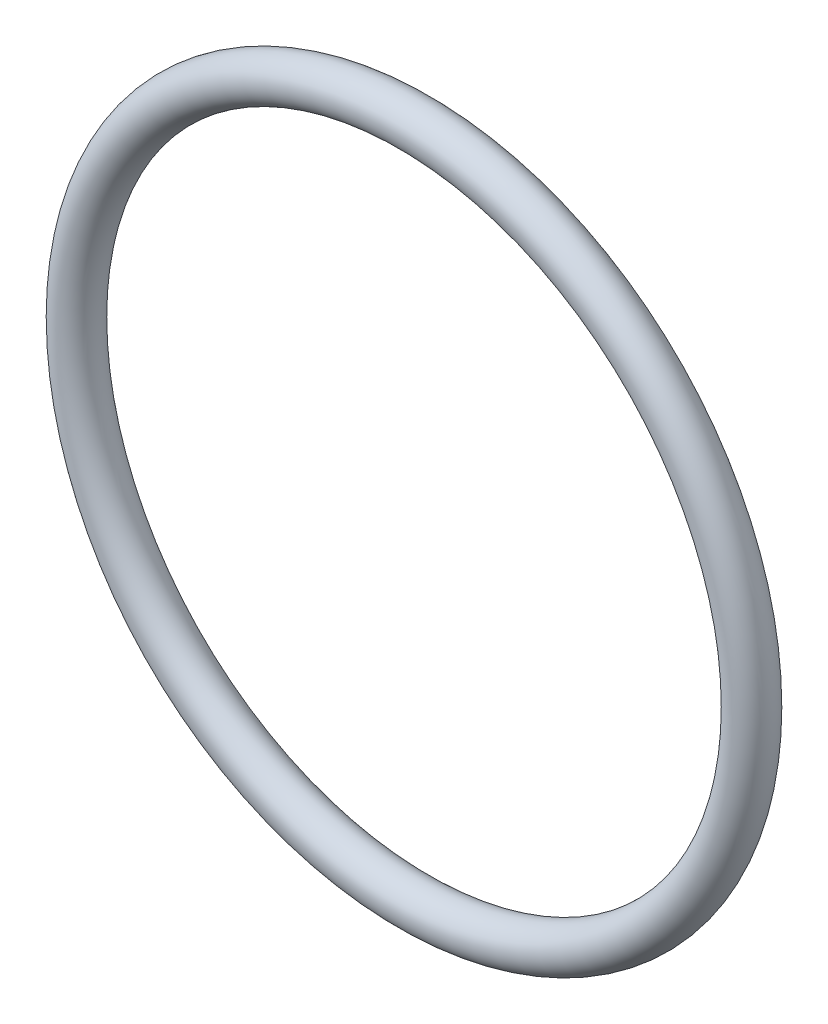
SolidWorks part; units mm, degrees
ref_plane "Front" through (0, 0, 0) normal (0, 0, 1) x (1, 0, 0)
ref_plane "Top" through (0, 0, 0) normal (0, 1, 0) x (1, 0, 0)
ref_plane "Right" through (0, 0, 0) normal (1, 0, 0) x (0, 0, -1)
sketch "Sketch1" plane through (0, 0, 0) normal (1, 0, 0) x (0, -1, 0)
  line L0 (0, -2.667) -> (0, 2.667) construction
  line L2 (-33.2346, 0) -> (33.2346, 0) construction
  line L3 (-39.37, 0) -> (39.37, 0) construction
  circle A0 centre (42.037, 0) radius 2.667
  point P9 (39.37, 0)
  point P10 (44.704, 0)
  point P13 (42.037, 2.667)
  point P14 (42.037, -2.667)
  dimension "Width" = 5.334
  dimension "ID" = 78.74
revolve "Revolve1" add sketch "Sketch1" angle 360 about L0
